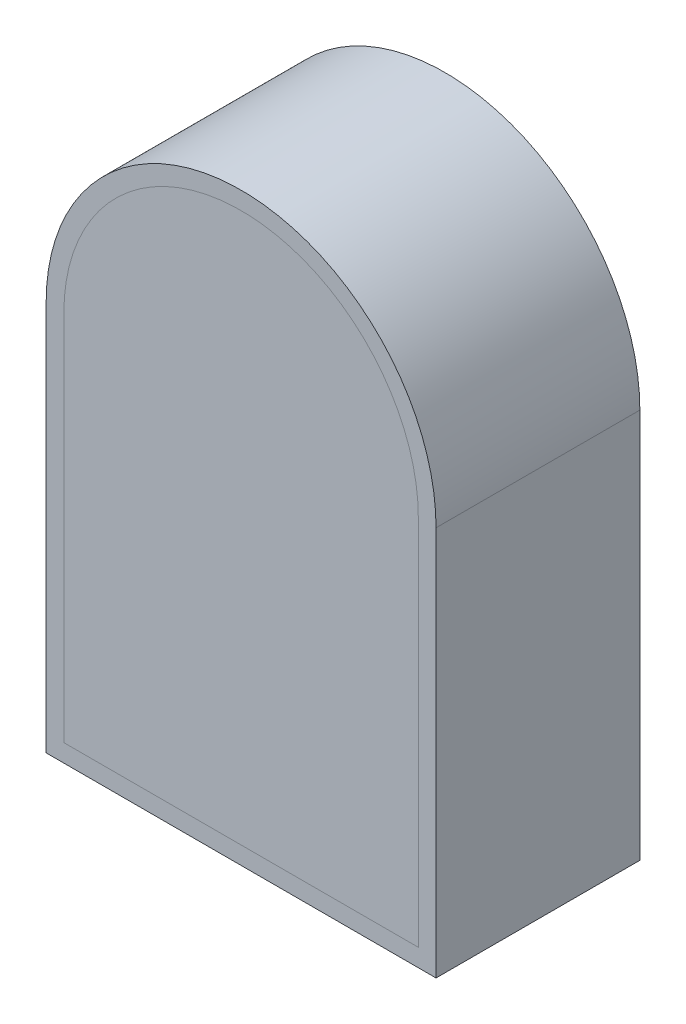
SolidWorks part; units mm, degrees
ref_plane "Plan de face" through (0, 0, 0) normal (0, 0, 1) x (1, 0, 0)
ref_plane "Plan de dessus" through (0, 0, 0) normal (0, 1, 0) x (1, 0, 0)
ref_plane "Plan de droite" through (0, 0, 0) normal (1, 0, 0) x (0, 0, -1)
sketch "Esquisse1" plane through (0, 0, 0) normal (0, 0, 1) x (1, 0, 0)
  line L0 (-11, 0) -> (11, 0)
  line L2 (-11, 0) -> (-11, 22)
  line L3 (11, 0) -> (11, 22)
  arc A0 (11, 22) -> (-11, 22) centre (0, 22) ccw
  point P4 (0, 0)
extrude "Boss.-Extru.1" add sketch "Esquisse1" along normal blind 11.5
sketch "Esquisse2" plane through (0, 0, 11.5) normal (0, 0, 1) x (1, 0, 0)
  line L3 (-10, 1) -> (-10, 22)
  line L5 (10, 22) -> (10, 1)
  line L6 (10, 1) -> (-10, 1)
  arc A0 (-10, 22) -> (10, 22) centre (0, 22) cw
extrude "Enlèv. mat.-Extru.1" cut sketch "Esquisse2" against normal blind 7.5
surface "Surface-Plan1"
